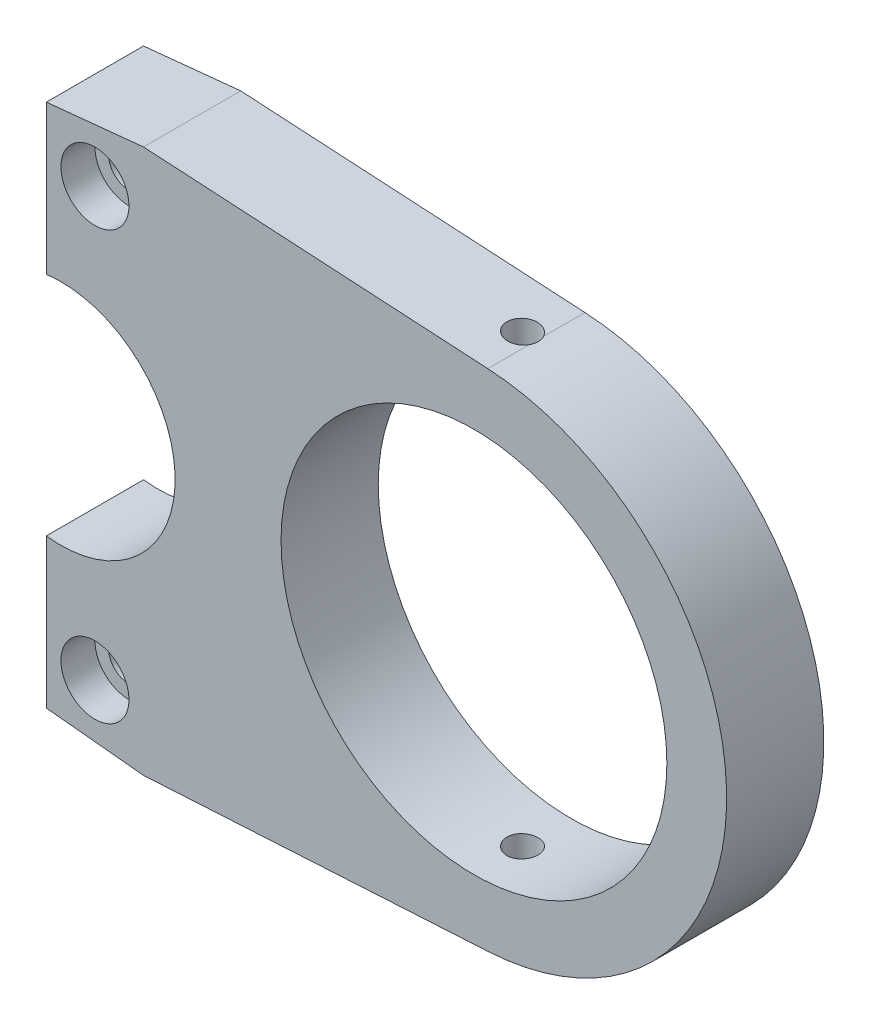
SolidWorks part; units mm, degrees
ref_plane "Front Plane" through (0, 0, 0) normal (0, 0, 1) x (1, 0, 0)
ref_plane "Top Plane" through (0, 0, 0) normal (0, 1, 0) x (1, 0, 0)
ref_plane "Right Plane" through (0, 0, 0) normal (1, 0, 0) x (0, 0, -1)
sketch "Sketch1" plane through (0, 0, 0) normal (0, 0, 1) x (1, 0, 0)
  line L0 (0, 0) -> (-76.6834, 0) construction
  line L4 (-24.9607, 0) -> (-25, 0)
  line L5 (-34, 28) -> (1.4186, 25.9614)
  line L7 (-34, -28) -> (1.4186, -25.9614)
  line L9 (0, 25) -> (0, -25) construction
  line L10 (-44, 27) -> (-44, -27)
  line L12 (-44, 25) -> (-44, -25) construction
  line L19 (-34, -28) -> (-44, -27)
  line L22 (-34, 28) -> (-44, 27)
  circle A0 centre (0, 0) radius 19.85
  arc A3 (1.4186, -25.9614) -> (1.4186, 25.9614) centre (0, 0) ccw
  point P4 (0, 14)
  point P6 (-78.8806, 14)
  point P7 (0, -14)
  point P8 (-78.8806, -14)
  point P9 (-20.7123, 14)
  point P10 (0, 27)
  point P13 (-35, 38.0468)
  point P14 (-76.6834, 27)
  point P15 (-35, -32.1096)
  point P16 (0, -27)
  point P17 (-76.6834, -27)
  point P18 (0, 28)
  point P19 (-76.6834, 28)
  point P21 (-20.7123, -14)
  point P22 (0, -28)
  point P23 (-76.6834, -28)
  point P31 (-35, 28)
  point P32 (-35, -28)
  dimension "D1" = 39.7
  dimension "D2" = 26.0001
  dimension "D3" = 54
  dimension "D4" = 56
  dimension "D5" = 45.4186
  dimension "D6" = 27
  dimension "D7" = 10
  dimension "D8" = 34
extrude "Boss-Extrude1" add sketch "Sketch1" along normal blind 10
sketch "Sketch2" plane through (0, 0, 10) normal (0, 0, 1) x (1, 0, 0)
  line L0 (-44, 27) -> (-44, -27) construction
  line L1 (-42.5, 27) -> (-42.5, -27) construction
  line L2 (-44, 0) -> (0, 0) construction
  line L3 (-54.25, 0) -> (-54.25, 19.6854) construction
  circle A0 centre (-42.5, 0) radius 11.75
  dimension "D2" = 23.5
  dimension "D1" = 1.5
extrude "Cut-Extrude1" cut sketch "Sketch2" against normal blind 10
ref_plane "Plane1" through (0, 0, 0) normal (0, 1, 0) x (1, 0, 0)
sketch "Sketch3" plane through (0, 0, 0) normal (0, 1, 0) x (1, 0, 0)
  line L0 (-34, -10) -> (1.4186, -10) construction
  line L1 (26.0001, -10) -> (26.0001, 0) construction
  circle A0 centre (0, -5) radius 1.6
  dimension "D1" = 3.2
  dimension "D2" = 5
  dimension "D3" = 26.0001
extrude "Cut-Extrude2" cut sketch "Sketch3" against normal mid plane 54
cosmetic thread "Cosmetic Thread1" parameters "D2"=4
cosmetic thread "Cosmetic Thread2" parameters "D2"=4
cosmetic thread "Cosmetic Thread3" parameters "D2"=4
sketch "Sketch4" plane through (0, 0, 10) normal (0, 0, 1) x (1, 0, 0)
  line L0 (-44, -11.6539) -> (-44, -27) construction
  line L1 (-44, 27) -> (-44, 11.6539) construction
  circle A0 centre (-39, 22) radius 2.1
  circle A1 centre (-39, -22) radius 2.1
  dimension "D2" = 5
  dimension "D3" = 5
  dimension "D4" = 5
  dimension "D5" = 4.2
  dimension "D6" = 4.2
  dimension "D1" = 5
extrude "Cut-Extrude3" cut sketch "Sketch4" against normal up to surface (10 mm away) up to face at (19.85, 0, 0)
sketch "Sketch5" plane through (0, 0, 10) normal (0, 0, 1) x (1, 0, 0)
  circle A0 centre (-39, 22) radius 3.5
  circle A1 centre (-39, -22) radius 3.5
  dimension "D1" = 7
  dimension "D2" = 7
extrude "Cut-Extrude4" cut sketch "Sketch5" against normal blind 3.5
